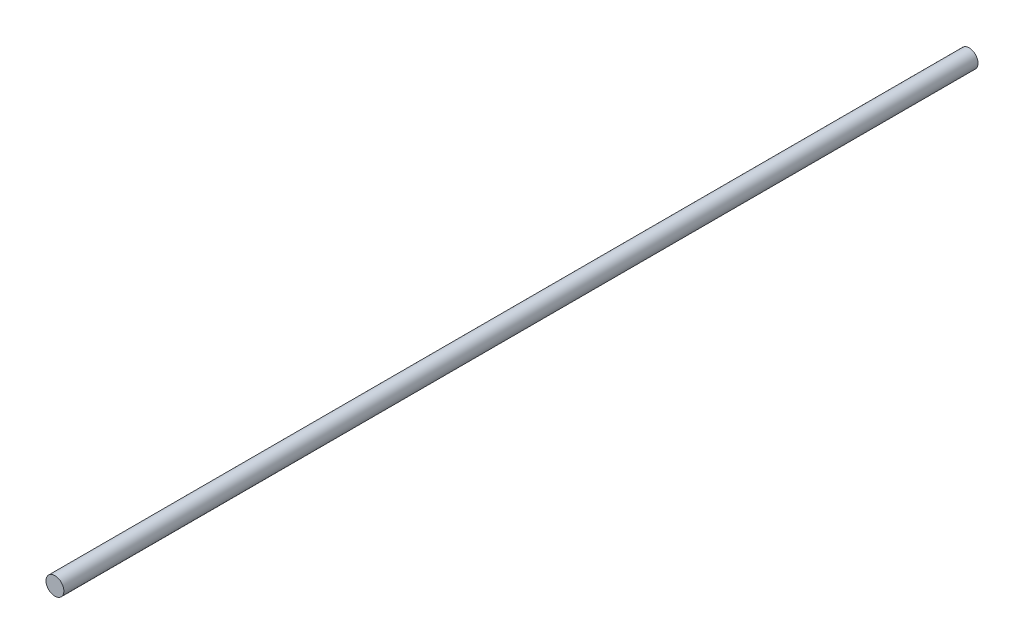
SolidWorks part; units mm, degrees
ref_plane "Front Plane" through (0, 0, 0) normal (0, 0, 1) x (1, 0, 0)
ref_plane "Top Plane" through (0, 0, 0) normal (0, 1, 0) x (1, 0, 0)
ref_plane "Right Plane" through (0, 0, 0) normal (1, 0, 0) x (0, 0, -1)
sketch "Sketch1" plane through (0, 0, 0) normal (0, 0, 1) x (1, 0, 0)
  circle A0 centre (0, 0) radius 4
  dimension "D1" = 8
extrude "Boss-Extrude1" add sketch "Sketch1" along normal blind 410
